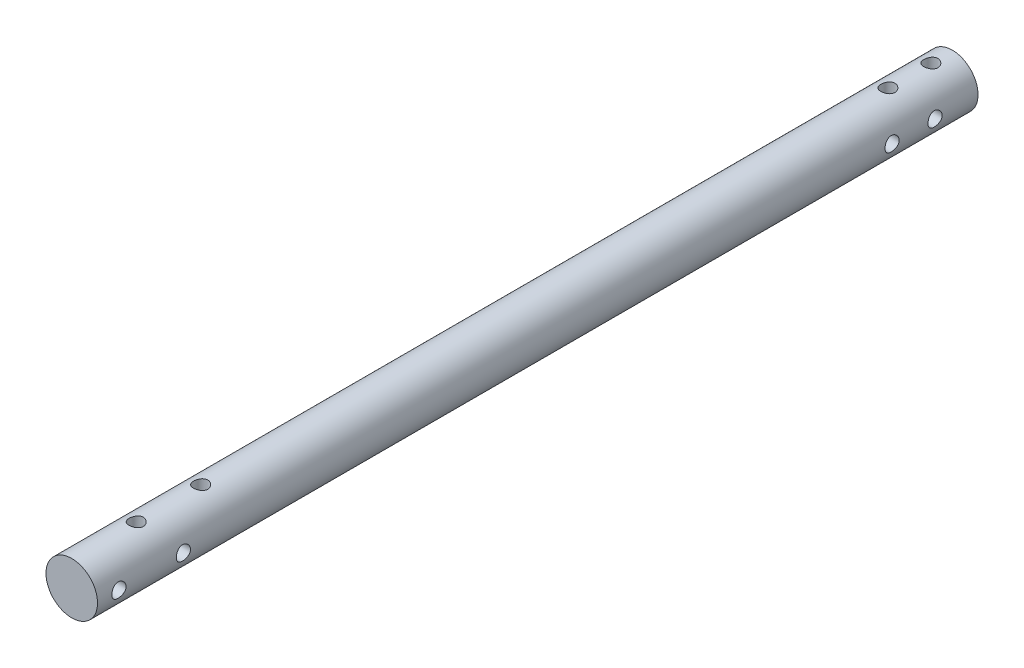
SolidWorks part; units mm, degrees
material "Thornel Mat VMA"
ref_plane "前视基准面" through (0, 0, 0) normal (0, 0, 1) x (1, 0, 0)
ref_plane "上视基准面" through (0, 0, 0) normal (0, 1, 0) x (1, 0, 0)
ref_plane "右视基准面" through (0, 0, 0) normal (1, 0, 0) x (0, 0, -1)
other "Configuration Table"
sketch "草图1" plane through (0, 0, 0) normal (0, 0, 1) x (1, 0, 0)
  line L1 (-4, 4) -> (4, 4)
  line L2 (-4, 4) -> (-4, -4)
  line L3 (-4, -4) -> (4, -4)
  line L4 (4, 4) -> (4, -4)
  line L5 (-4, 4) -> (4, -4) construction
  line L6 (-4, -4) -> (4, 4) construction
  line L7 (-2, 2) -> (2, 2)
  line L8 (-2, 2) -> (-2, -2)
  line L9 (-2, -2) -> (2, -2)
  line L10 (2, 2) -> (2, -2)
  line L11 (-2, 2) -> (2, -2) construction
  line L12 (-2, -2) -> (2, 2) construction
  point P0 (0, 0)
  point P6 (0, 0)
  dimension "D1" = 2
  dimension "D2" = 8
  dimension "D3" = 8
extrude "凸台-拉伸1" add sketch "草图1" along normal blind 205
sketch "草图7" plane through (0, 0, 0) normal (0, 0, -1) x (-1, 0, 0)
  circle A0 centre (0, 0) radius 6
  dimension "D1" = 12
extrude "凸台-拉伸2" add sketch "草图7" against normal blind 205
sketch "草图2" plane through (0, 0, 0) normal (0, 1, 0) x (1, 0, 0)
  line L1 (6, 0) -> (-6, 0) construction
  circle A0 centre (0, -5) radius 1.65
  circle A1 centre (0, -15) radius 1.65
  dimension "D1" = 10
  dimension "D2" = 3.3
  dimension "D3" = 5
extrude "切除-拉伸1" cut sketch "草图2" against normal through all both and the other way through all
sketch "草图3" plane through (0, 0, 0) normal (-1, 0, 0) x (0, 0, 1)
  line L0 (0, 0) -> (23.2715, 0) construction
  line L2 (10, 0) -> (20, 0) construction
  line L3 (0, 6) -> (0, -6) construction
  circle A1 centre (10, 0) radius 1.65
  circle A2 centre (20, 0) radius 1.65
  dimension "D1" = 3.3
  dimension "D2" = 2
  dimension "D3" = 10
  dimension "D4" = 10
extrude "切除-拉伸2" cut sketch "草图3" against normal through all both and the other way through all
sketch "草图4" plane through (0, 0, 0) normal (-1, 0, 0) x (0, 0, 1)
  line L1 (205, -6) -> (205, 6) construction
  circle A0 centre (200, 0) radius 1.65
  circle A1 centre (185, 0) radius 1.65
  dimension "D1" = 5
  dimension "D2" = 15
  dimension "D3" = 3.3
extrude "切除-拉伸3" cut sketch "草图4" against normal through all both and the other way through all
sketch "草图5" plane through (0, 0, 0) normal (0, 1, 0) x (1, 0, 0)
  line L1 (-6, -205) -> (6, -205) construction
  circle A0 centre (0, -190) radius 1.65
  circle A1 centre (0, -175) radius 1.65
  dimension "D1" = 15
  dimension "D2" = 15
  dimension "D3" = 3.3
extrude "切除-拉伸4" cut sketch "草图5" against normal through all both and the other way through all
sketch "草图8" plane through (0, 0, 0) normal (1, 0, 0) x (0, 0, -1)
  line L1 (-205, 6) -> (0, 6)
  line L2 (-205, 6) -> (-205, -6)
  line L3 (-205, -6) -> (0, -6)
  line L4 (0, 6) -> (0, -6)
  circle A0 centre (-20, 0) radius 1.65 construction
  circle A1 centre (-10, 0) radius 1.65 construction
  circle A2 centre (-185, 0) radius 1.65 construction
  circle A3 centre (-200, 0) radius 1.65 construction
  circle A4 centre (-20, 0) radius 1.65
  circle A5 centre (-10, 0) radius 1.65
  circle A6 centre (-185, 0) radius 1.65
  circle A7 centre (-200, 0) radius 1.65
extrude "凸台-拉伸3" [suppressed] add sketch "草图8" along normal blind 10
sketch "草图10" plane through (0, 0, 0) normal (0, 1, 0) x (1, 0, 0)
  line L0 (6, 0) -> (-6, 0) construction
  line L1 (-6, 0) -> (6, 0)
  line L2 (-6, 0) -> (-6, -205)
  line L3 (-6, -205) -> (6, -205)
  line L4 (6, 0) -> (6, -205)
  circle A0 centre (0, -5) radius 1.65 construction
  circle A1 centre (0, -190) radius 1.65 construction
  circle A2 centre (0, -175) radius 1.65 construction
  circle A3 centre (0, -15) radius 1.65 construction
  circle A4 centre (0, -190) radius 1.65
  circle A5 centre (0, -175) radius 1.65
  circle A6 centre (0, -15) radius 1.65
  circle A7 centre (0, -5) radius 1.65
  point P19 (-6, -205)
extrude "凸台-拉伸4" [suppressed] add sketch "草图10" along normal blind 10
